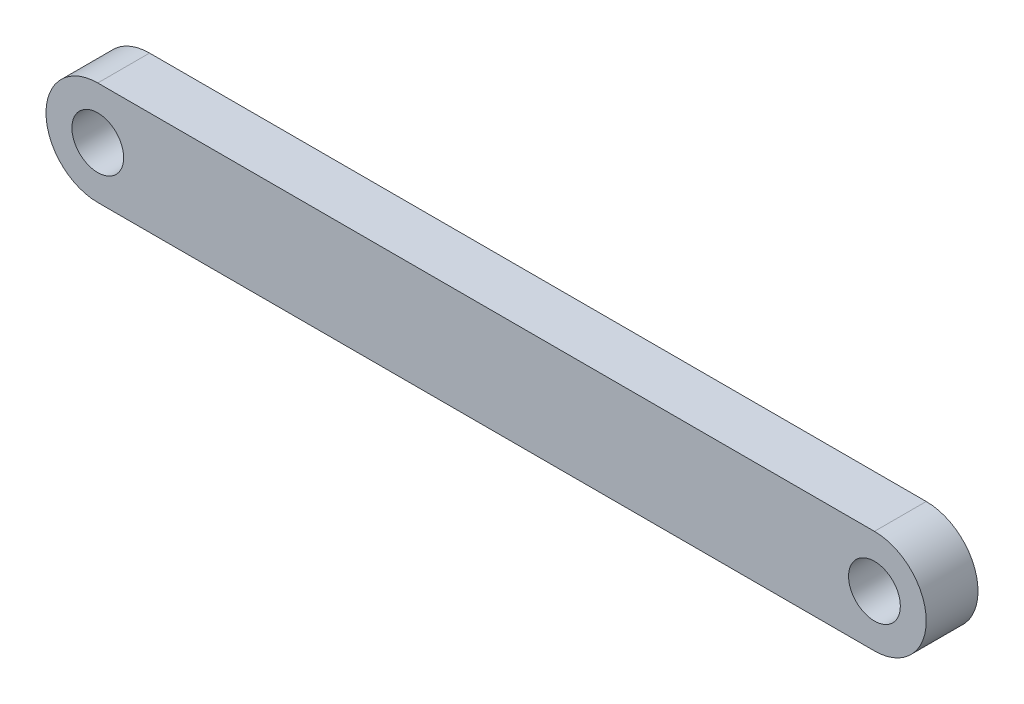
SolidWorks part; units mm, degrees
ref_plane "Front Plane" through (0, 0, 0) normal (0, 0, 1) x (1, 0, 0)
ref_plane "Top Plane" through (0, 0, 0) normal (0, 1, 0) x (1, 0, 0)
ref_plane "Right Plane" through (0, 0, 0) normal (1, 0, 0) x (0, 0, -1)
sketch "Sketch1" plane through (0, 0, 0) normal (0, 0, 1) x (1, 0, 0)
  line L0 (-75, 0) -> (75, 0) construction
  line L1 (-75, 10) -> (75, 10)
  line L2 (-75, -10) -> (75, -10)
  arc A1 (-75, 10) -> (-75, -10) centre (-75, 0) ccw
  arc A2 (75, -10) -> (75, 10) centre (75, 0) ccw
  circle A3 centre (-75, 0) radius 5
  circle A4 centre (75, 0) radius 5
  point P3 (0, 0)
  dimension "D1" = 150
  dimension "D3" = 10
  dimension "D4" = 10
  dimension "D2" = 20
extrude "Boss-Extrude3" add sketch "Sketch1" along normal blind 10
sketch "Sketch2" plane through (0, 0, 0) normal (0, 0, 1) x (1, 0, 0)
  point P0 (-75, 0)
  point P1 (75, 0)
